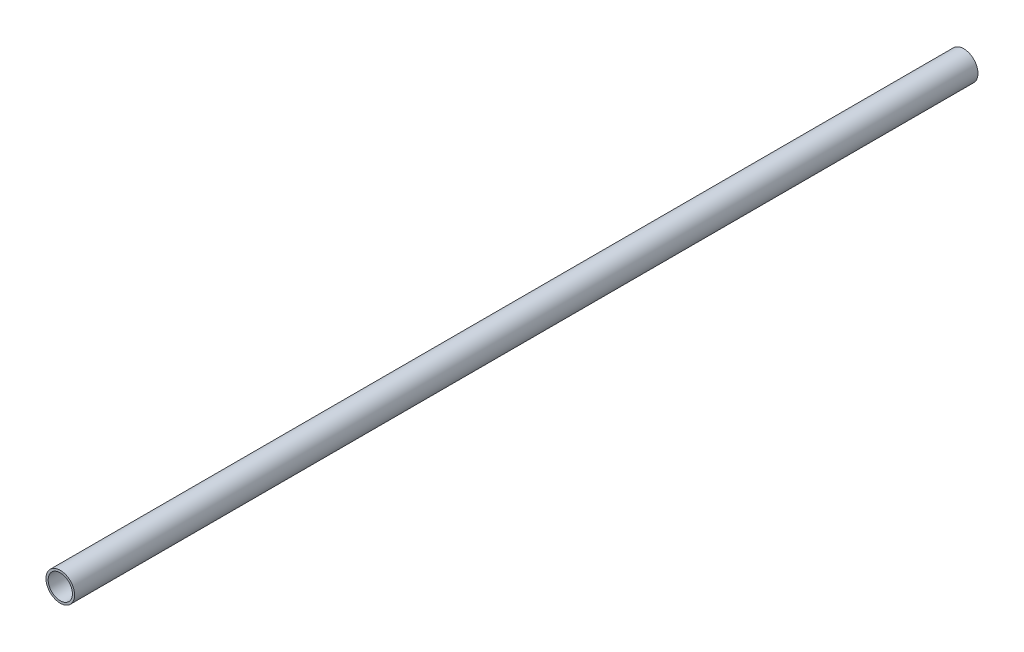
SolidWorks part; units mm, degrees
ref_plane "Front Plane" through (0, 0, 0) normal (0, 0, 1) x (1, 0, 0)
ref_plane "Top Plane" through (0, 0, 0) normal (0, 1, 0) x (1, 0, 0)
ref_plane "Right Plane" through (0, 0, 0) normal (1, 0, 0) x (0, 0, -1)
sketch "Sketch1" plane through (0, 0, 0) normal (1, 0, 0) x (0, 0, -1)
  line L0 (-762, 0) -> (762, 0) construction
  line L1 (762, 24.13) -> (762, -24.13) construction
  line L2 (-762, 24.13) -> (-762, -24.13) construction
  circle A0 centre (-762, 0) radius 20.447 construction
  point P0 (0, 0)
  point P9 (-762, 20.447)
  point P10 (-665.48, 0)
  point P11 (-762, -20.447)
  point P12 (665.48, 0)
  point P16 (-762, -24.13)
  dimension "Length" = 1524
  dimension "OD" = 48.26
  dimension "Pipe Size" = 48.26
  dimension "Wall Thickness" = 3.683
  dimension "ID" = 40.894
  dimension "D1" = 96.52
  dimension "D2" = 96.52
sketch "Sketch3" plane through (0, 0, 0) normal (0, 0, 1) x (1, 0, 0)
  circle A0 centre (0, 0) radius 24.13
  circle A1 centre (0, 0) radius 20.447
  point P4 (-24.13, 0)
  point P6 (24.13, 0)
  point P8 (0, 24.13)
  point P9 (0, -24.13)
  point P10 (0, 20.447)
  point P11 (-20.447, 0)
  point P12 (20.447, 0)
extrude "Boss-Extrude1" add sketch "Sketch3" against normal up to vertex (762 mm away) and the other way up to vertex (762 mm away) up to point (0, 24.13, -762) other way up to point (0, 24.13, 762)
equation "\"D1@Sketch1\"=\"OD@Sketch1\"*2"
equation "\"D2@Sketch1\"=\"D1@Sketch1\""
